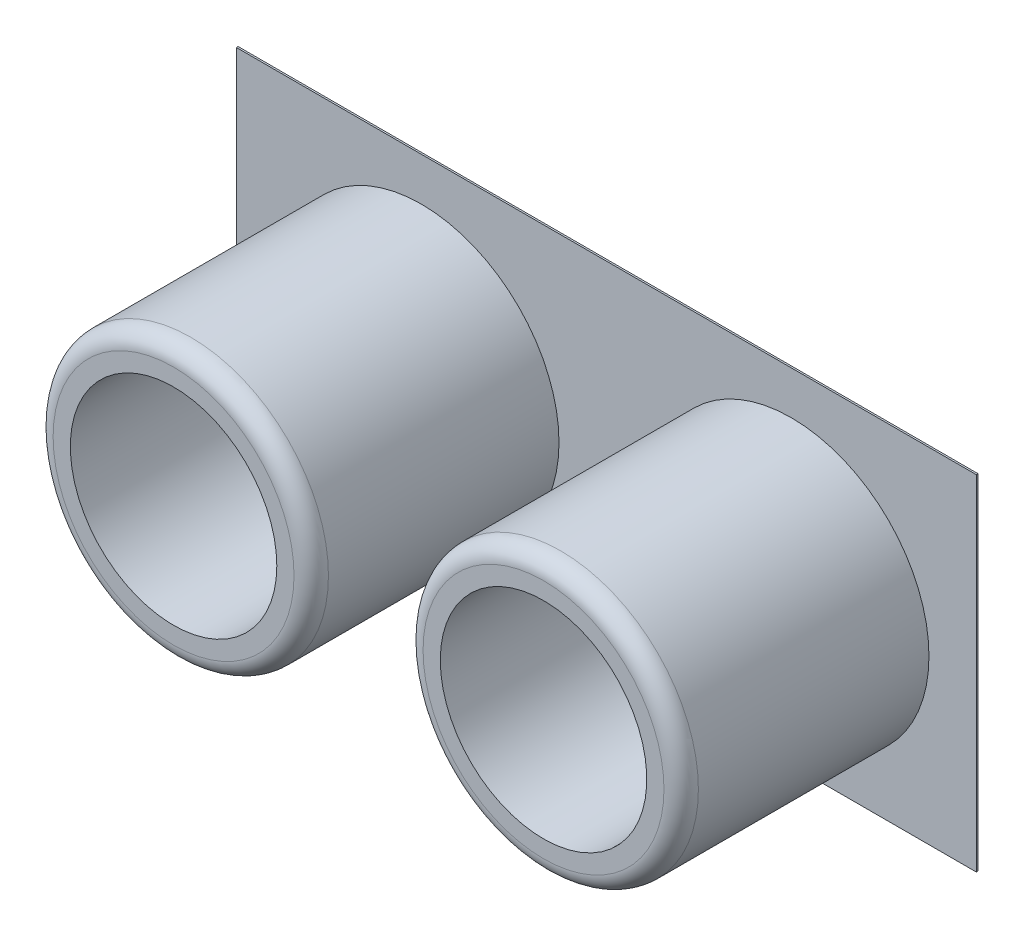
SolidWorks part; units mm, degrees
ref_plane "Front Plane" through (0, 0, 0) normal (0, 0, 1) x (1, 0, 0)
ref_plane "Top Plane" through (0, 0, 0) normal (0, 1, 0) x (1, 0, 0)
ref_plane "Right Plane" through (0, 0, 0) normal (1, 0, 0) x (0, 0, -1)
sketch "Sketch1" plane through (0, 0, 0) normal (0, 0, 1) x (1, 0, 0)
  line L0 (-29.5527, 0) -> (34.0091, 0) construction
  line L1 (0, 19.6627) -> (0, -20.8355) construction
  line L3 (-21.5, 10.5082) -> (21.5, 10.5082)
  line L4 (-21.5, 10.5082) -> (-21.5, -9.4918)
  line L5 (-21.5, -9.4918) -> (21.5, -9.4918)
  line L6 (21.5, 10.5082) -> (21.5, -9.4918)
  line L7 (-21.5, 10.5082) -> (21.5, -9.4918) construction
  line L8 (-21.5, -9.4918) -> (21.5, 10.5082) construction
  point P5 (0, 0.5082)
  dimension "D1" = 43
  dimension "D2" = 20
extrude "Boss-Extrude1" add sketch "Sketch1" along normal blind 0.1
sketch "Sketch3" plane through (0, 0, 0.1) normal (0, 0, 1) x (1, 0, 0)
  line L0 (-22.6611, 0) -> (25.7671, 0) construction
  line L1 (0, 16.4528) -> (0, -16.7106) construction
  line L2 (-10.75, 16.4528) -> (-10.75, -16.7106) construction
  circle A0 centre (-10.75, 0) radius 8
  circle A1 centre (10.75, 0) radius 8
  dimension "D1" = 10.75
extrude "Boss-Extrude2" add sketch "Sketch3" along normal blind 14.4
fillet "Fillet1" radius 1 2 edges at (-2.75, 0, 14.5) (2.75, 0, 14.5)
sketch "Sketch5" plane through (0, 0, 14.5) normal (0, 0, 1) x (1, 0, 0)
  line L0 (-22.974, 0) -> (25.4176, 0) construction
  line L1 (0, 18.6128) -> (0, -18.8005) construction
  line L2 (-10.75, 18.0666) -> (-10.75, -18.8005) construction
  circle A0 centre (-10.75, 0) radius 6
  circle A1 centre (10.75, 0) radius 6
  point P12 (0, 0)
  dimension "D2" = 12
  dimension "D1" = 10.75
extrude "Cut-Extrude1" cut sketch "Sketch5" against normal blind 10
sketch "Sketch6" plane through (0, 0, 0) normal (0, 0, -1) x (-1, 0, 0)
  line L0 (-24.7501, 0) -> (29.3218, 0) construction
  line L1 (0, 15.3625) -> (0, -14.732) construction
  line L2 (-2.54, 15.3625) -> (-2.54, -14.732) construction
  line L3 (1.27, 15.3625) -> (1.27, -14.732) construction
  line L4 (-24.7501, -7.7918) -> (29.3218, -7.7918) construction
  line L5 (21.5, -9.4918) -> (-21.5, -9.4918) construction
  line L7 (-1.27, -6.5218) -> (3.81, -6.5218)
  line L8 (-1.27, -6.5218) -> (-1.27, -9.0618)
  line L9 (-1.27, -9.0618) -> (3.81, -9.0618)
  line L10 (1.27, -6.5218) -> (1.27, -9.0618)
  line L11 (-1.27, -6.5218) -> (1.27, -9.0618) construction
  line L12 (-1.27, -9.0618) -> (1.27, -6.5218) construction
  line L16 (6.35, -9.0618) -> (3.81, -9.0618)
  line L17 (-3.81, -6.5218) -> (-1.27, -6.5218)
  line L18 (-3.81, -6.5218) -> (-3.81, -9.0618)
  line L19 (-3.81, -9.0618) -> (-1.27, -9.0618)
  line L20 (-1.27, -6.5218) -> (-1.27, -9.0618)
  line L21 (-3.81, -6.5218) -> (-1.27, -9.0618) construction
  line L22 (-3.81, -9.0618) -> (-1.27, -6.5218) construction
  line L23 (3.81, -6.5218) -> (3.81, -9.0618)
  line L24 (6.35, -6.5218) -> (3.81, -6.5218)
  line L25 (6.35, -6.5218) -> (6.35, -9.0618)
  line L26 (3.81, -6.5218) -> (3.81, -9.0618)
  line L28 (-3.81, -6.5218) -> (6.35, -6.5218)
  line L29 (-3.81, -6.5218) -> (-3.81, -9.0618)
  line L30 (-3.81, -9.0618) -> (6.35, -9.0618)
  line L31 (6.35, -6.5218) -> (6.35, -9.0618)
  point P13 (0, -7.7918)
  point P18 (-2.54, -7.7918)
  dimension "D1" = 1.27
  dimension "D2" = 2.54
  dimension "D3" = 1.7
  dimension "D4" = 2.54
  dimension "D5" = 2.54
  dimension "D6" = 2.54
  dimension "D7" = 10.16
